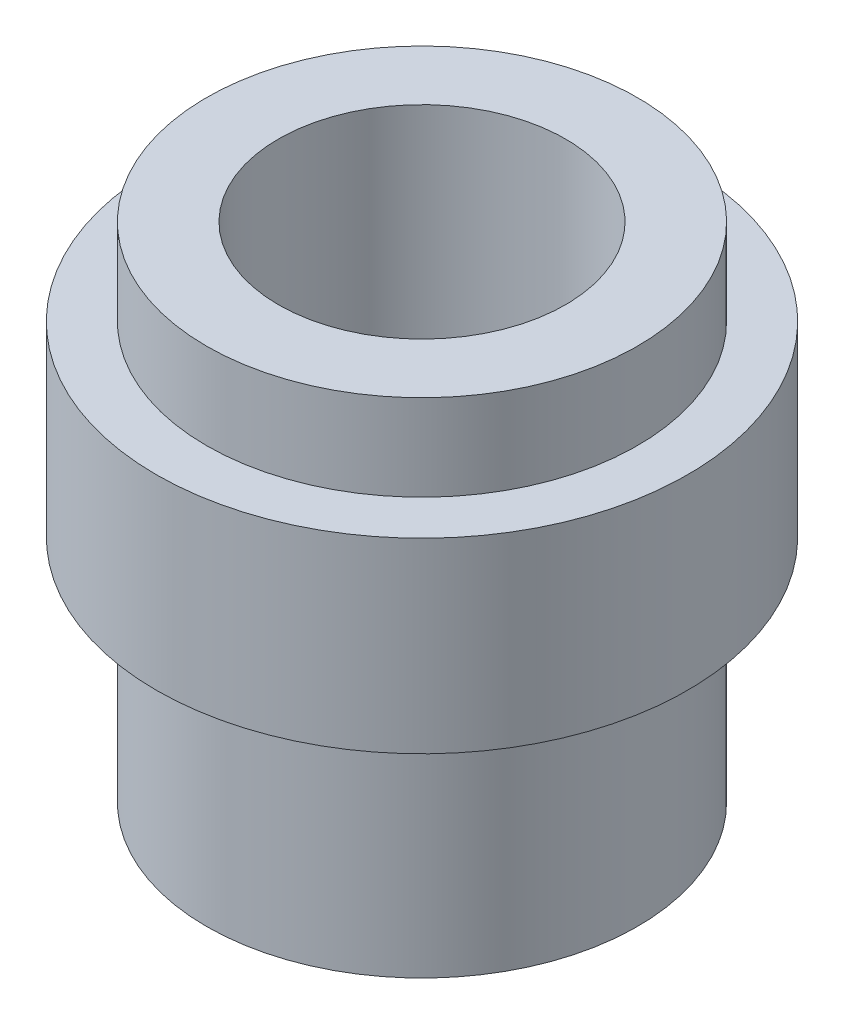
SolidWorks part; units mm, degrees
ref_plane "Спереди" through (0, 0, 0) normal (0, 0, 1) x (1, 0, 0)
ref_plane "Сверху" through (0, 0, 0) normal (0, 1, 0) x (1, 0, 0)
ref_plane "Справа" through (0, 0, 0) normal (1, 0, 0) x (0, 0, -1)
sketch "Эскиз1" plane through (0, 0, 0) normal (0, 0, 1) x (1, 0, 0)
  line L0 (0, 46.5034) -> (0, -53.198) construction
  line L1 (0, 37.5814) -> (15, 37.5814)
  line L2 (15, 37.5814) -> (15, 31.5814)
  line L3 (15, 31.5814) -> (18.5, 31.5814)
  line L4 (18.5, 31.5814) -> (18.5, 18.5814)
  line L5 (18.5, 18.5814) -> (15, 18.5814)
  line L6 (15, 18.5814) -> (15, 2.5814)
  line L7 (15, 2.5814) -> (0, 2.5814)
  line L8 (0, 37.5814) -> (0, 2.5814)
  dimension "D1" = 15
  dimension "D2" = 15
  dimension "D3" = 18.5
  dimension "D4" = 6
  dimension "D5" = 13
  dimension "D6" = 16
  dimension "D7" = 35
revolve "Повернуть1" add sketch "Эскиз1" angle 360 about L0
sketch "Эскиз2" plane through (0, 37.5814, 0) normal (0, 1, 0) x (1, 0, 0)
  circle A0 centre (0, 0) radius 10
  dimension "D1" = 20
extrude "Вырез-Вытянуть1" cut sketch "Эскиз2" against normal blind 45
